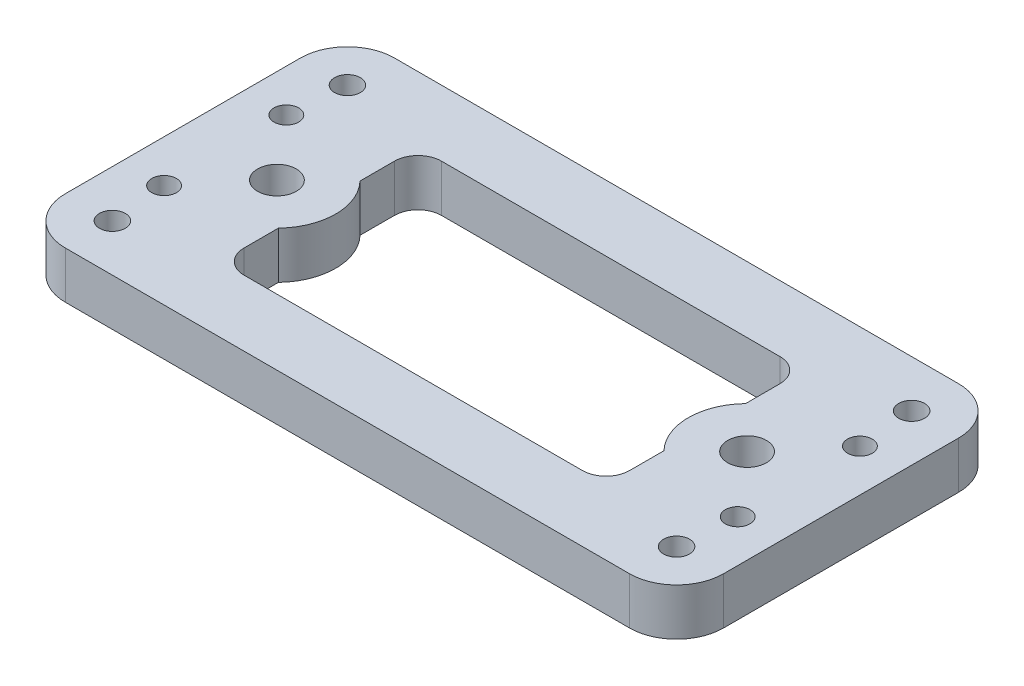
SolidWorks part; units mm, degrees
material "Pine"
ref_plane "Front Plane" through (0, 0, 0) normal (0, 0, 1) x (1, 0, 0)
ref_plane "Top Plane" through (0, 0, 0) normal (0, 1, 0) x (1, 0, 0)
ref_plane "Right Plane" through (0, 0, 0) normal (1, 0, 0) x (0, 0, -1)
sketch "Sketch1" plane through (0, 0, 0) normal (0, 1, 0) x (1, 0, 0)
  line L1 (-41, 21) -> (41, 21)
  line L2 (-41, 21) -> (-41, -21)
  line L3 (-41, -21) -> (41, -21)
  line L4 (41, 21) -> (41, -21)
  line L5 (-41, 21) -> (41, -21) construction
  line L6 (-41, -21) -> (41, 21) construction
  line L7 (-70, 35) -> (70, 35)
  line L8 (-70, 35) -> (-70, -35)
  line L9 (-70, -35) -> (70, -35)
  line L10 (70, 35) -> (70, -35)
  line L11 (-70, 35) -> (70, -35) construction
  line L12 (-70, -35) -> (70, 35) construction
  point P0 (0, 0)
  point P6 (0, 0)
  dimension "D1" = 29
  dimension "D2" = 14
  dimension "D3" = 140
  dimension "D4" = 70
extrude "Boss-Extrude1" add sketch "Sketch1" along normal blind 10
fillet "Fillet1" radius 10 4 edges at (70, 5, 35) (70, 5, -35) (-70, 5, -35) (-70, 5, 35)
sketch "Sketch2" plane through (0, 10, 0) normal (0, 1, 0) x (1, 0, 0)
  line L0 (-60, -35) -> (60, -35) construction
  line L1 (-70, 25) -> (-70, -25) construction
  line L2 (0, 0) -> (0, 48.6702) construction
  line L3 (0, 0) -> (23.6821, 0) construction
  circle A0 centre (-60, -25) radius 2.75
  circle A1 centre (-60, 25) radius 2.75
  circle A2 centre (60, -25) radius 2.75
  circle A3 centre (60, 25) radius 2.75
  dimension "D1" = 5.5
  dimension "D2" = 10
  dimension "D3" = 10
extrude "Cut-Extrude1" cut sketch "Sketch2" against normal through all
sketch "Sketch3" plane through (0, 10, 0) normal (0, 1, 0) x (1, 0, 0)
  line L0 (0, 0) -> (0, 59.0273) construction
  line L1 (-70, 25) -> (-70, -25) construction
  circle A0 centre (-50, 0) radius 4.125
  circle A1 centre (50, 0) radius 4.125
  dimension "D1" = 8.25
  dimension "D2" = 20
extrude "Cut-Extrude2" cut sketch "Sketch3" against normal through all
sketch "Sketch4" plane through (0, 10, 0) normal (0, 1, 0) x (1, 0, 0)
  line L0 (0, 0) -> (0, 50.6676) construction
  line L1 (-41, 21) -> (-41, -21) construction
  line L2 (-41, 8.6747) -> (-41, -8.6747)
  line L3 (41, 8.6747) -> (41, -8.6747)
  arc A0 (-41, 8.6747) -> (-41, -8.6747) centre (-50, 0) cw
  arc A1 (41, 8.6747) -> (41, -8.6747) centre (50, 0) ccw
  dimension "D1" = 12.5
extrude "Boss-Extrude2" add sketch "Sketch4" against normal up to vertex (10 mm away)
fillet "Fillet2" radius 5 4 edges at (41, 5, 21) (41, 5, -21) (-41, 5, 21) (-41, 5, -21)
sketch "Sketch5" plane through (0, 10, 0) normal (0, 1, 0) x (1, 0, 0)
  circle A0 centre (-61, 13) radius 2.625
  circle A1 centre (-61, 13) radius 2.625 construction
  circle A2 centre (-61, -13) radius 2.625
  circle A3 centre (-61, -13) radius 2.625 construction
  circle A4 centre (61, 13) radius 2.625
  circle A5 centre (61, -13) radius 2.625
  circle A6 centre (61, 13) radius 2.625 construction
  circle A7 centre (61, -13) radius 2.625 construction
extrude "Cut-Extrude3" cut sketch "Sketch5" against normal through all
